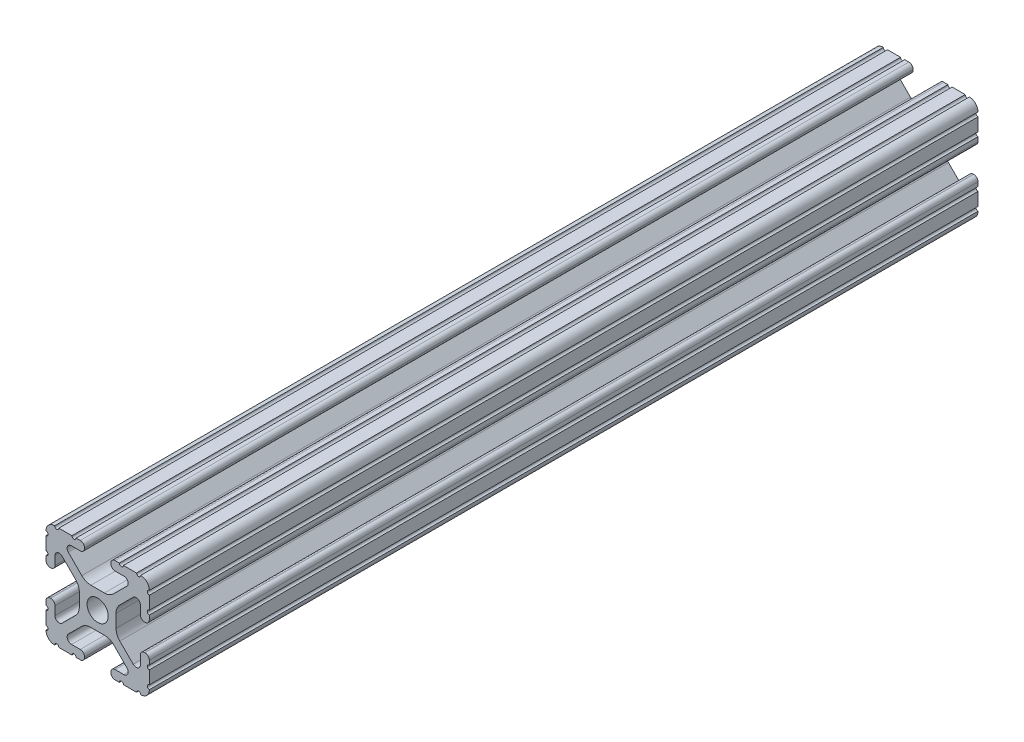
SolidWorks part; units mm, degrees
ref_plane "Front Plane" through (0, 0, 0) normal (0, 0, 1) x (1, 0, 0)
ref_plane "Top Plane" through (0, 0, 0) normal (0, 1, 0) x (1, 0, 0)
ref_plane "Right Plane" through (0, 0, 0) normal (1, 0, 0) x (0, 0, -1)
sketch "Sketch1" plane through (0, 0, 0) normal (0, 0, 1) x (1, 0, 0)
  line L0 (-7.207, 8.7244) -> (-3.8983, 5.4232)
  line L1 (-4.2875, 10.4902) -> (-6.4768, 10.4902)
  line L2 (-3.2385, 11.651) -> (-3.2385, 11.5392)
  line L3 (-5.3171, 12.7) -> (-4.2875, 12.7)
  line L4 (0, 13.4005) -> (0, -14.8534) construction
  line L5 (12.7, 0) -> (-13.9989, 0) construction
  line L6 (-9.5504, 12.7) -> (-6.3331, 12.7)
  line L7 (-12.7, 6.3331) -> (-12.7, 9.5504)
  line L8 (-12.7, 4.2875) -> (-12.7, 5.3171)
  line L9 (-11.5392, 3.2385) -> (-11.651, 3.2385)
  line L10 (-10.4902, 6.4021) -> (-10.4902, 4.2875)
  line L11 (-5.441, 3.8408) -> (-8.7371, 7.1294)
  line L12 (-4.5085, -1.5932) -> (-4.5085, 1.5932)
  line L13 (-1.7093, -4.4958) -> (1.7093, -4.4958)
  line L14 (3.9523, -5.4237) -> (7.1797, -8.6452)
  line L15 (6.4164, -10.4902) -> (4.2875, -10.4902)
  line L16 (3.2385, -11.5392) -> (3.2385, -11.651)
  line L17 (4.2875, -12.7) -> (5.3171, -12.7)
  line L18 (6.3331, -12.7) -> (9.5504, -12.7)
  line L19 (12.7, -9.5504) -> (12.7, -6.3331)
  line L20 (12.7, -5.3171) -> (12.7, -4.2875)
  line L21 (11.651, -3.2385) -> (11.5392, -3.2385)
  line L22 (10.4902, -4.2875) -> (10.4902, -6.4021)
  line L23 (8.7371, -7.1294) -> (5.441, -3.8408)
  line L24 (4.5085, -1.5932) -> (4.5085, 1.5932)
  line L25 (5.441, 3.8408) -> (8.7371, 7.1294)
  line L26 (10.4902, 6.4021) -> (10.4902, 4.2875)
  line L27 (11.5392, 3.2385) -> (11.651, 3.2385)
  line L28 (12.7, 4.2875) -> (12.7, 5.3171)
  line L29 (12.7, 6.3331) -> (12.7, 9.5504)
  line L30 (9.5504, 12.7) -> (6.3331, 12.7)
  line L31 (5.3171, 12.7) -> (4.2875, 12.7)
  line L32 (3.2385, 11.651) -> (3.2385, 11.5392)
  line L33 (4.2875, 10.4902) -> (6.4768, 10.4902)
  line L34 (7.207, 8.7244) -> (3.8983, 5.4232)
  line L35 (1.6558, 4.4958) -> (-1.6558, 4.4958)
  line L36 (-8.7371, -7.1294) -> (-5.441, -3.8408)
  line L37 (-10.4902, -4.2875) -> (-10.4902, -6.4021)
  line L38 (-11.651, -3.2385) -> (-11.5392, -3.2385)
  line L39 (-12.7, -5.3171) -> (-12.7, -4.2875)
  line L40 (-12.7, -9.5504) -> (-12.7, -6.3331)
  line L41 (-6.3331, -12.7) -> (-9.5504, -12.7)
  line L42 (-4.2875, -12.7) -> (-5.3171, -12.7)
  line L43 (-3.2385, -11.5392) -> (-3.2385, -11.651)
  line L44 (-6.4164, -10.4902) -> (-4.2875, -10.4902)
  line L45 (-3.9523, -5.4237) -> (-7.1797, -8.6452)
  arc A0 (-7.207, 8.7244) -> (-6.4768, 10.4902) centre (-6.4768, 9.4563) cw
  arc A1 (-3.2385, 11.5392) -> (-4.2875, 10.4902) centre (-4.2875, 11.5392) cw
  arc A2 (-4.2875, 12.7) -> (-3.2385, 11.651) centre (-4.2875, 11.651) cw
  arc A3 (-5.3171, 12.7) -> (-6.3331, 12.7) centre (-5.8251, 12.7) cw
  arc A4 (-9.5504, 12.7) -> (-10.5664, 12.6998) centre (-10.0584, 12.7) cw
  arc A5 (-12.6998, 10.5664) -> (-10.5664, 12.6998) centre (-10.5918, 10.5918) cw
  arc A6 (-12.6998, 10.5664) -> (-12.7, 9.5504) centre (-12.7, 10.0584) cw
  arc A7 (-12.7, 6.3331) -> (-12.7, 5.3171) centre (-12.7, 5.8251) cw
  arc A8 (-11.651, 3.2385) -> (-12.7, 4.2875) centre (-11.651, 4.2875) cw
  arc A9 (-10.4902, 4.2875) -> (-11.5392, 3.2385) centre (-11.5392, 4.2875) cw
  circle A10 centre (0, 0) radius 2.6035
  arc A11 (-10.4902, 6.4021) -> (-8.7371, 7.1294) centre (-9.4628, 6.4021) cw
  arc A12 (-5.441, 3.8408) -> (-4.5085, 1.5932) centre (-7.6835, 1.5932) cw
  arc A13 (-4.5085, -1.5932) -> (-5.441, -3.8408) centre (-7.6835, -1.5932) cw
  arc A14 (-8.7371, -7.1294) -> (-10.4902, -6.4021) centre (-9.4628, -6.4021) cw
  arc A15 (-1.7093, -4.4958) -> (-3.9523, -5.4237) centre (-1.7093, -7.6708) ccw
  arc A16 (3.9523, -5.4237) -> (1.7093, -4.4958) centre (1.7093, -7.6708) ccw
  arc A17 (6.4164, -10.4902) -> (7.1797, -8.6452) centre (6.4164, -9.4098) ccw
  arc A18 (4.2875, -10.4902) -> (3.2385, -11.5392) centre (4.2875, -11.5392) ccw
  arc A19 (3.2385, -11.651) -> (4.2875, -12.7) centre (4.2875, -11.651) ccw
  arc A20 (6.3331, -12.7) -> (5.3171, -12.7) centre (5.8251, -12.7) ccw
  arc A21 (10.5664, -12.6998) -> (9.5504, -12.7) centre (10.0584, -12.7) ccw
  arc A22 (10.5664, -12.6998) -> (12.6998, -10.5664) centre (10.5918, -10.5918) ccw
  arc A23 (12.7, -9.5504) -> (12.6998, -10.5664) centre (12.7, -10.0584) ccw
  arc A24 (12.7, -5.3171) -> (12.7, -6.3331) centre (12.7, -5.8251) ccw
  arc A25 (12.7, -4.2875) -> (11.651, -3.2385) centre (11.651, -4.2875) ccw
  arc A26 (11.5392, -3.2385) -> (10.4902, -4.2875) centre (11.5392, -4.2875) ccw
  arc A27 (8.7371, -7.1294) -> (10.4902, -6.4021) centre (9.4628, -6.4021) ccw
  arc A28 (4.5085, -1.5932) -> (5.441, -3.8408) centre (7.6835, -1.5932) ccw
  arc A29 (5.441, 3.8408) -> (4.5085, 1.5932) centre (7.6835, 1.5932) ccw
  arc A30 (10.4902, 6.4021) -> (8.7371, 7.1294) centre (9.4628, 6.4021) ccw
  arc A31 (10.4902, 4.2875) -> (11.5392, 3.2385) centre (11.5392, 4.2875) ccw
  arc A32 (11.651, 3.2385) -> (12.7, 4.2875) centre (11.651, 4.2875) ccw
  arc A33 (12.7, 6.3331) -> (12.7, 5.3171) centre (12.7, 5.8251) ccw
  arc A34 (12.6998, 10.5664) -> (12.7, 9.5504) centre (12.7, 10.0584) ccw
  arc A35 (12.6998, 10.5664) -> (10.5664, 12.6998) centre (10.5918, 10.5918) ccw
  arc A36 (9.5504, 12.7) -> (10.5664, 12.6998) centre (10.0584, 12.7) ccw
  arc A37 (5.3171, 12.7) -> (6.3331, 12.7) centre (5.8251, 12.7) ccw
  arc A38 (4.2875, 12.7) -> (3.2385, 11.651) centre (4.2875, 11.651) ccw
  arc A39 (3.2385, 11.5392) -> (4.2875, 10.4902) centre (4.2875, 11.5392) ccw
  arc A40 (7.207, 8.7244) -> (6.4768, 10.4902) centre (6.4768, 9.4563) ccw
  arc A41 (1.6558, 4.4958) -> (3.8983, 5.4232) centre (1.6558, 7.6708) ccw
  arc A42 (-1.6558, 4.4958) -> (-3.8983, 5.4232) centre (-1.6558, 7.6708) cw
  arc A43 (-11.5392, -3.2385) -> (-10.4902, -4.2875) centre (-11.5392, -4.2875) cw
  arc A44 (-12.7, -4.2875) -> (-11.651, -3.2385) centre (-11.651, -4.2875) cw
  arc A45 (-12.7, -5.3171) -> (-12.7, -6.3331) centre (-12.7, -5.8251) cw
  arc A46 (-12.7, -9.5504) -> (-12.6998, -10.5664) centre (-12.7, -10.0584) cw
  arc A47 (-10.5664, -12.6998) -> (-12.6998, -10.5664) centre (-10.5918, -10.5918) cw
  arc A48 (-10.5664, -12.6998) -> (-9.5504, -12.7) centre (-10.0584, -12.7) cw
  arc A49 (-6.3331, -12.7) -> (-5.3171, -12.7) centre (-5.8251, -12.7) cw
  arc A50 (-3.2385, -11.651) -> (-4.2875, -12.7) centre (-4.2875, -11.651) cw
  arc A51 (-4.2875, -10.4902) -> (-3.2385, -11.5392) centre (-4.2875, -11.5392) cw
  arc A52 (-6.4164, -10.4902) -> (-7.1797, -8.6452) centre (-6.4164, -9.4098) cw
  dimension "D1" = 5.207
  dimension "D9" = 14.859
  dimension "D2" = 25.4
  dimension "D3" = 12.7
  dimension "D4" = 6.477
  dimension "D5" = 8.2042
  dimension "D6" = 9.017
  dimension "D8" = 2.2098
  dimension "D10" = 2.2098
extrude "Extrude1" add sketch "Sketch1" against normal blind 203.2 and the other way blind 0.508
